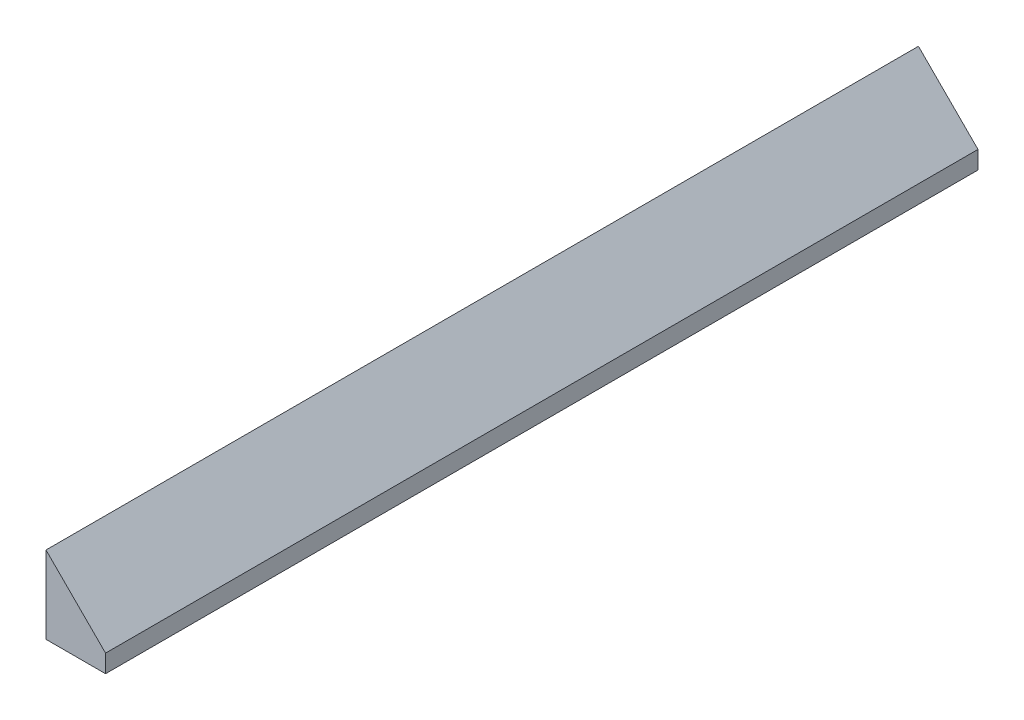
SolidWorks part; units mm, degrees
material "6061-T6 (SS)"
ref_plane "Front Plane" through (0, 0, 0) normal (0, 0, 1) x (1, 0, 0)
ref_plane "Top Plane" through (0, 0, 0) normal (0, 1, 0) x (1, 0, 0)
ref_plane "Right Plane" through (0, 0, 0) normal (1, 0, 0) x (0, 0, -1)
sketch "Sketch1" plane through (0, 0, 0) normal (0, 0, 1) x (1, 0, 0)
  line L5 (0, 0) -> (2.6, 0)
  line L6 (2.6, 0) -> (0, 2.6)
  line L7 (0, 2.6) -> (0, 0)
  line L11 (2, 0) -> (2, 0.6)
  dimension "D1" = 0.6
  dimension "D2" = 2.6
extrude "Boss-Extrude1" add sketch "Sketch1" against normal mid plane 29.3 contours L5 L11 L6 L7
